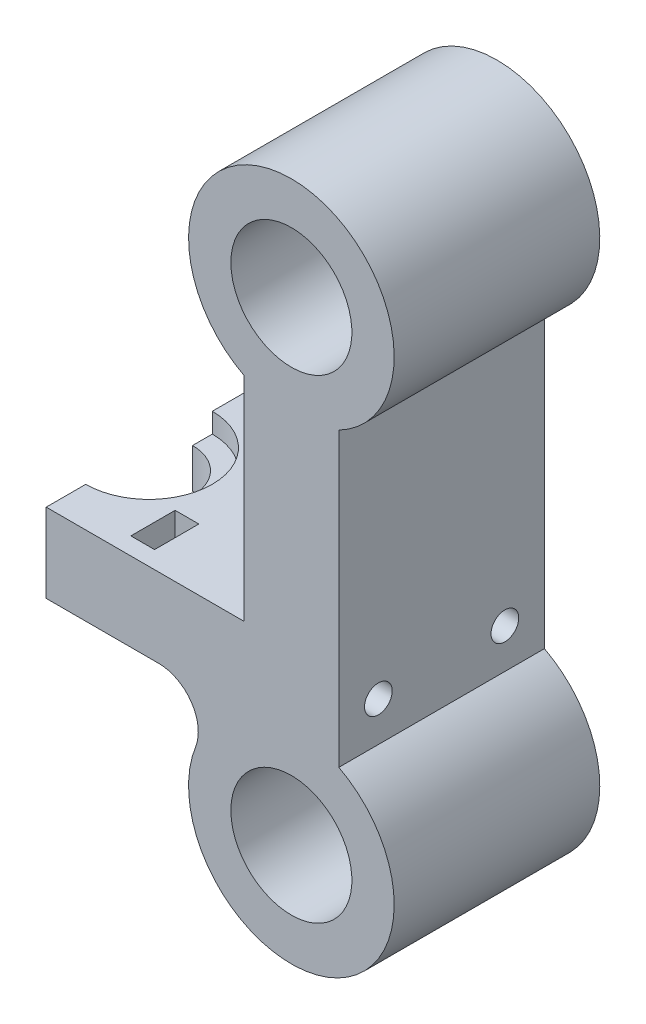
SolidWorks part; units mm, degrees
ref_plane "Plano frontal" through (0, 0, 0) normal (0, 0, 1) x (1, 0, 0)
ref_plane "Plano superior" through (0, 0, 0) normal (0, 1, 0) x (1, 0, 0)
ref_plane "Plano direito" through (0, 0, 0) normal (1, 0, 0) x (0, 0, -1)
sketch "Esboço1" plane through (0, 0, 0) normal (0, 0, 1) x (1, 0, 0)
  line L0 (0, 30) -> (0, -30) construction
  line L1 (-6, 18.4674) -> (-6, -8.4674)
  line L2 (6, 18.4674) -> (6, -18.4674)
  line L3 (-6, 30) -> (-6, -30) construction
  line L4 (6, 30) -> (6, -30) construction
  line L5 (-16.7728, -18.4674) -> (-31, -18.4674)
  line L6 (-31, -18.4674) -> (-31, -8.4674)
  line L7 (-31, -8.4674) -> (-6, -8.4674)
  circle A0 centre (0, 30) radius 7.65
  circle A1 centre (0, -30) radius 7.65
  arc A2 (6, 18.4674) -> (-6, 18.4674) centre (0, 30) ccw
  arc A3 (-12.1137, -25.282) -> (6, -18.4674) centre (0, -30) ccw
  arc A4 (-16.7728, -18.4674) -> (-12.1137, -25.282) centre (-16.7728, -23.4674) cw
  point P4 (0, 0)
  dimension "D3" = 60
  dimension "D4" = 15.3
  dimension "D5" = 26
  dimension "D8" = 5
  dimension "D6" = 25
  dimension "D7" = 10
  dimension "D1" = 6
  dimension "D2" = 6
extrude "Ressalto-extrusão1" add sketch "Esboço1" along normal blind 26
sketch "Esboço3" plane through (-31, 0, 0) normal (-1, 0, 0) x (0, 0, 1)
  line L0 (13, -8.4674) -> (13, -18.4674) construction
  line L1 (26, -8.4674) -> (0, -8.4674) construction
  line L2 (26, -18.4674) -> (0, -18.4674) construction
  line L3 (13, -8.4674) -> (21, -8.4674)
  line L4 (21, -8.4674) -> (21, -10.9674)
  line L5 (21, -10.9674) -> (18.5, -10.9674)
  line L6 (18.5, -10.9674) -> (18.5, -15.9674)
  line L7 (18.5, -15.9674) -> (21, -15.9674)
  line L8 (21, -15.9674) -> (21, -18.4674)
  line L9 (26, -18.4674) -> (0, -18.4674) construction
  line L10 (21, -18.4674) -> (13, -18.4674)
  line L11 (13, -8.4674) -> (13, -18.4674)
  point P6 (18.5, -13.4674)
  dimension "D1" = 5
  dimension "D2" = 5.5
  dimension "D3" = 8
revolve "Corte-Revolução1" cut sketch "Esboço3" angle 360 about L0
sketch "Esboço4" plane through (-31, 0, 0) normal (-1, 0, 0) x (0, 0, 1)
  line L0 (13, -8.4674) -> (13, -18.4674) construction
  line L1 (26, -8.4674) -> (0, -8.4674) construction
  line L3 (7.5, -10.9674) -> (7.5, -15.9674) construction
  circle A0 centre (5, -13.4674) radius 1.75
  circle A1 centre (21, -13.4674) radius 1.75
  point P8 (0, 0)
  point P11 (7.5, -13.4674)
  point P14 (0, 0)
  dimension "D2" = 3.5
  dimension "D1" = 16
extrude "Corte-extrusão1" cut sketch "Esboço4" against normal through all
sketch "Esboço5" plane through (0, -8.4674, 0) normal (0, 1, 0) x (1, 0, 0)
  line L0 (-31, -5) -> (-21, -5) construction
  line L1 (-31, -5) -> (-31, 0) construction
  line L2 (-22.5, -2.2) -> (-19.5, -2.2)
  line L3 (-22.5, -2.2) -> (-22.5, -7.8)
  line L4 (-22.5, -7.8) -> (-19.5, -7.8)
  line L5 (-19.5, -2.2) -> (-19.5, -7.8)
  line L6 (-22.5, -2.2) -> (-19.5, -7.8) construction
  line L7 (-22.5, -7.8) -> (-19.5, -2.2) construction
  line L8 (-31, -13) -> (-16.3815, -13) construction
  line L9 (-22.5, -18.2) -> (-19.5, -23.8) construction
  line L10 (-22.5, -23.8) -> (-19.5, -18.2) construction
  line L11 (-31, -21) -> (-21, -21) construction
  line L12 (-19.5, -23.8) -> (-19.5, -18.2)
  line L13 (-22.5, -18.2) -> (-19.5, -18.2)
  line L14 (-22.5, -23.8) -> (-22.5, -18.2)
  line L15 (-22.5, -23.8) -> (-19.5, -23.8)
  dimension "D1" = 10
  dimension "D2" = 5.6
  dimension "D3" = 3
  dimension "D4" = 16
extrude "Corte-extrusão2" cut sketch "Esboço5" against normal blind 25
